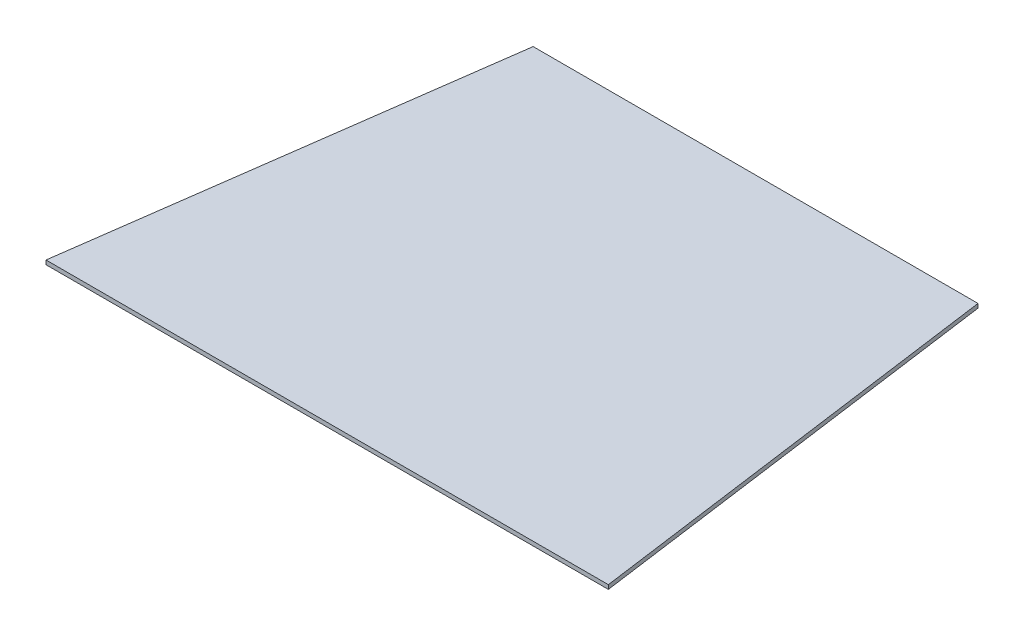
SolidWorks part; units mm, degrees
ref_plane "Front Plane" through (0, 0, 0) normal (0, 0, 1) x (1, 0, 0)
ref_plane "Top Plane" through (0, 0, 0) normal (0, 1, 0) x (1, 0, 0)
ref_plane "Right Plane" through (0, 0, 0) normal (1, 0, 0) x (0, 0, -1)
sketch "Sketch1" plane through (0, 0, 0) normal (0, 1, 0) x (1, 0, 0)
  line L1 (-118.406, 92.8469) -> (135.594, 92.8469)
  line L2 (-118.406, 92.8469) -> (-118.406, -72.2531)
  line L3 (-118.406, -72.2531) -> (135.594, -72.2531)
  line L4 (135.594, 92.8469) -> (135.594, -72.2531)
  dimension "D1" = 254
  dimension "D2" = 165.1
extrude "Boss-Extrude1" add sketch "Sketch1" along normal blind 1.5875
sketch "Sketch2" plane through (0, 1.5875, 0) normal (0, 1, 0) x (1, 0, 0)
  line L0 (-118.406, 92.8469) -> (-77.131, 92.8469)
  line L1 (135.594, 92.8469) -> (-118.406, 92.8469) construction
  line L2 (-77.131, 92.8469) -> (-99.7745, -72.2531)
  line L3 (-118.406, -72.2531) -> (135.594, -72.2531) construction
  line L4 (-99.7745, -72.2531) -> (-118.406, -72.2531)
  line L5 (-118.406, -72.2531) -> (-118.406, 92.8469)
  line L6 (135.594, 92.8469) -> (94.319, 92.8469)
  line L7 (94.319, 92.8469) -> (116.9625, -72.2531)
  line L8 (116.9625, -72.2531) -> (135.594, -72.2531)
  line L9 (135.594, -72.2531) -> (135.594, 92.8469) construction
  line L10 (135.594, -72.2531) -> (135.594, 92.8469)
  dimension "D1" = 41.275
  dimension "D2" = 41.275
  dimension "D3" = 18.6315
extrude "Cut-Extrude1" cut sketch "Sketch2" against normal blind 1.5875
